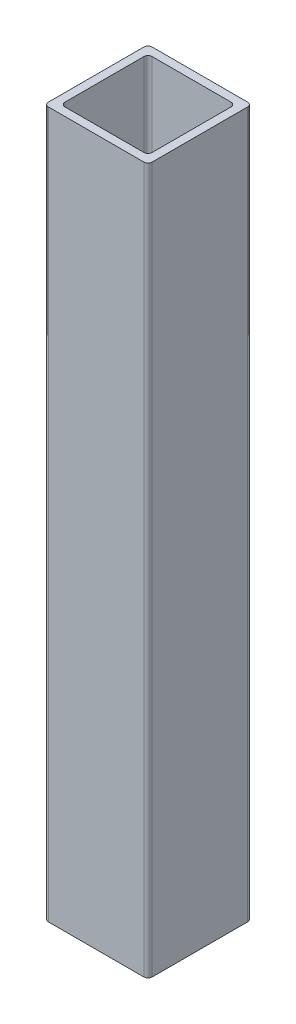
SolidWorks part; units mm, degrees
material "Hexcel AS4C (3000 Filaments)"
ref_plane "Front Plane" through (0, 0, 0) normal (0, 0, 1) x (1, 0, 0)
ref_plane "Top Plane" through (0, 0, 0) normal (0, 1, 0) x (1, 0, 0)
ref_plane "Right Plane" through (0, 0, 0) normal (1, 0, 0) x (0, 0, -1)
sketch "Sketch1" plane through (0, 0, 0) normal (0, 1, 0) x (1, 0, 0)
  line L1 (-11.5, -12.5) -> (11.5, -12.5)
  line L2 (-12.5, -11.5) -> (-12.5, 11.5)
  line L3 (-11.5, 12.5) -> (11.5, 12.5)
  line L4 (12.5, -11.5) -> (12.5, 11.5)
  line L5 (-12.5, -12.5) -> (12.5, 12.5) construction
  line L6 (-12.5, 12.5) -> (12.5, -12.5) construction
  line L7 (-9.5, -10.5) -> (9.5, -10.5)
  line L8 (-10.5, -9.5) -> (-10.5, 9.5)
  line L9 (-9.5, 10.5) -> (9.5, 10.5)
  line L10 (10.5, -9.5) -> (10.5, 9.5)
  line L11 (-10.5, -10.5) -> (10.5, 10.5) construction
  line L12 (-10.5, 10.5) -> (10.5, -10.5) construction
  arc A0 (-11.5, -12.5) -> (-12.5, -11.5) centre (-11.5, -11.5) cw
  arc A1 (11.5, 12.5) -> (12.5, 11.5) centre (11.5, 11.5) cw
  arc A2 (11.5, -12.5) -> (12.5, -11.5) centre (11.5, -11.5) ccw
  arc A3 (-12.5, 11.5) -> (-11.5, 12.5) centre (-11.5, 11.5) cw
  arc A4 (-9.5, -10.5) -> (-10.5, -9.5) centre (-9.5, -9.5) cw
  arc A5 (9.5, -10.5) -> (10.5, -9.5) centre (9.5, -9.5) ccw
  arc A6 (9.5, 10.5) -> (10.5, 9.5) centre (9.5, 9.5) cw
  arc A7 (-10.5, 9.5) -> (-9.5, 10.5) centre (-9.5, 9.5) cw
  point P0 (0, 0)
  point P18 (0, 0)
  dimension "D3" = 1
  dimension "D6" = 1
  dimension "D7" = 1
  dimension "D8" = 1
  dimension "D9" = 1
  dimension "D1" = 25
  dimension "D2" = 25
  dimension "D4" = 21
  dimension "D5" = 21
extrude "Boss-Extrude1" add sketch "Sketch1" along normal blind 170
